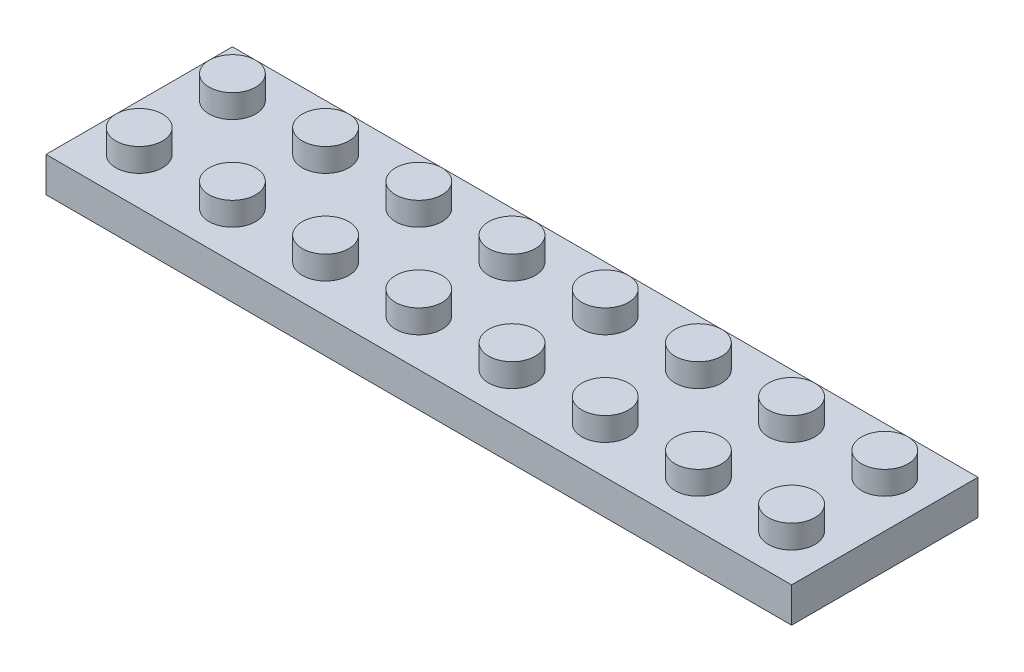
SolidWorks part; units mm, degrees
ref_plane "Front Plane" through (0, 0, 0) normal (0, 0, 1) x (1, 0, 0)
ref_plane "Top Plane" through (0, 0, 0) normal (0, 1, 0) x (1, 0, 0)
ref_plane "Right Plane" through (0, 0, 0) normal (1, 0, 0) x (0, 0, -1)
sketch "Sketch2" plane through (0, 0, 0) normal (0, 1, 0) x (1, 0, 0)
  line L1 (-32, 8) -> (32, 8)
  line L2 (-32, 8) -> (-32, -8)
  line L3 (-32, -8) -> (32, -8)
  line L4 (32, 8) -> (32, -8)
  line L5 (-32, 8) -> (32, -8) construction
  line L6 (-32, -8) -> (32, 8) construction
  point P0 (0, 0)
  dimension "D1" = 64
  dimension "D2" = 16
extrude "Boss-Extrude1" add sketch "Sketch2" along normal blind 3
sketch "Sketch3" plane through (0, 3, 0) normal (0, 1, 0) x (1, 0, 0)
  line L0 (32, 8) -> (-32, 8) construction
  line L1 (-32, 8) -> (-32, -8) construction
  line L2 (-28, 4) -> (-28, -4) construction
  circle A0 centre (-28, 4) radius 2
  circle A1 centre (-20, 4) radius 2
  circle A2 centre (-12, 4) radius 2
  circle A3 centre (-4, 4) radius 2
  circle A4 centre (4, 4) radius 2
  circle A5 centre (12, 4) radius 2
  circle A6 centre (20, 4) radius 2
  circle A7 centre (28, 4) radius 2
  circle A8 centre (-20, -4) radius 2
  circle A9 centre (-12, -4) radius 2
  circle A10 centre (-4, -4) radius 2
  circle A11 centre (4, -4) radius 2
  circle A12 centre (12, -4) radius 2
  circle A13 centre (20, -4) radius 2
  circle A14 centre (28, -4) radius 2
  circle A15 centre (-28, -4) radius 2
  dimension "D1" = 4
  dimension "D2" = 4
  dimension "D3" = 4
  dimension "D6" = 8
  dimension "D4" = 8
  dimension "D5" = 2
extrude "Boss-Extrude2" add sketch "Sketch3" along normal blind 2
shell "Shell1" thickness 1
sketch "Sketch4" plane through (0, 2, 0) normal (0, -1, 0) x (1, 0, 0)
  line L0 (-32, -8) -> (-32, 8) construction
  line L1 (-32, 8) -> (32, 8) construction
  circle A0 centre (-24, 0) radius 1.8
  circle A1 centre (-24, 0) radius 2.8
  point P3 (0, 0)
  point P5 (0, 0)
  dimension "D1" = 5.6
  dimension "D2" = 3.6
  dimension "D3" = 8
  dimension "D4" = 8
extrude "Boss-Extrude3" add sketch "Sketch4" along normal blind 2
pattern_linear "LPattern2" count 7 spacing 8 along (1, 0, 0) of "Boss-Extrude3"
